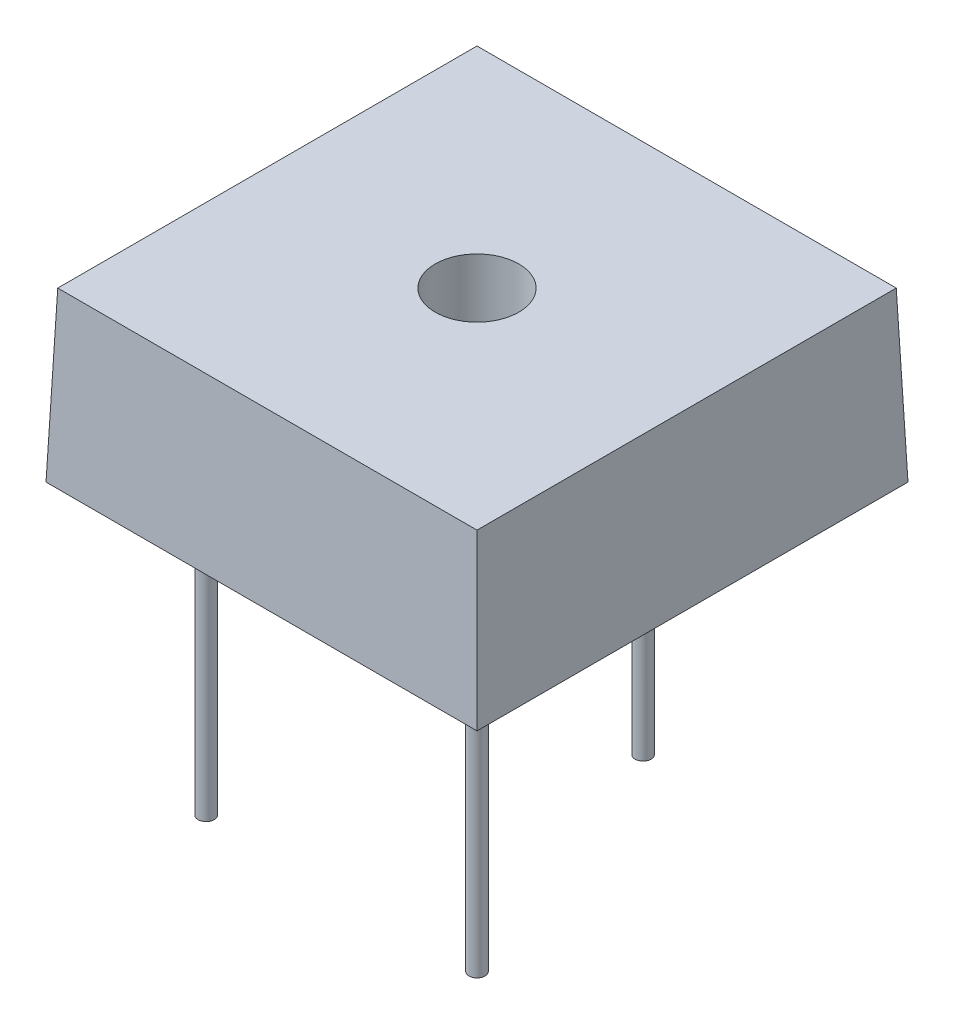
SolidWorks part; units mm, degrees
ref_plane "Front" through (0, 0, 0) normal (0, 0, 1) x (1, 0, 0)
ref_plane "Top" through (0, 0, 0) normal (0, 1, 0) x (1, 0, 0)
ref_plane "Right" through (0, 0, 0) normal (1, 0, 0) x (0, 0, -1)
sketch "Sketch1" plane through (0, 0, 0) normal (0, 1, 0) x (1, 0, 0)
  line L0 (0, 0) -> (0, 14.4) construction
  line L1 (0, 0) -> (14.4, 0) construction
  line L2 (14.4, -14.4) -> (14.4, 14.4)
  line L3 (-14.4, -14.4) -> (-14.4, 14.4)
  line L4 (-14.4, -14.4) -> (14.4, -14.4)
  line L5 (-14.4, 14.4) -> (14.4, 14.4)
  line L6 (0, 14.4) -> (14.4, 14.4) construction
  line L7 (0, -14.4) -> (14.4, -14.4) construction
  line L8 (-14.4, 0) -> (-14.4, 14.4) construction
  line L9 (14.4, 0) -> (14.4, 14.4) construction
  dimension "D1" = 14.4
  dimension "D2" = 14.4
  dimension "D3" = 14.4
  dimension "D4" = 14.4
extrude "Boss-Extrude1" add sketch "Sketch1" along normal blind 11.23 draft 2 contours L5 L3 L4 L2
sketch "Sketch2" plane through (0, 0, 0) normal (0, -1, 0) x (1, 0, 0)
  line L14 (-13.4, -13.4) -> (13.4, -13.4)
  line L15 (13.4, -13.4) -> (13.4, 13.4)
  line L16 (13.4, 13.4) -> (-13.4, 13.4)
  line L17 (-13.4, 13.4) -> (-13.4, -13.4)
  line L18 (-13.4, -13.4) -> (13.4, -13.4)
  line L19 (13.4, -13.4) -> (13.4, 13.4)
  line L20 (13.4, 13.4) -> (-13.4, 13.4)
  line L21 (-13.4, 13.4) -> (-13.4, -13.4)
  circle A0 centre (0, 0) radius 2.795 construction
  circle A1 centre (0, 0) radius 3.795
  dimension "D2" = 5.59
  dimension "D1" = 1
  dimension "D3" = 1
extrude "Cut-Extrude1" cut sketch "Sketch2" against normal blind 0.5
sketch "Sketch3" plane through (0, 0, 0) normal (0, -1, 0) x (1, 0, 0)
  circle A2 centre (0, 0) radius 2.795
  circle A3 centre (0, 0) radius 2.795
  dimension "D1" = 1
extrude "Cut-Extrude2" cut sketch "Sketch3" against normal through all
sketch "Sketch4" plane through (0, 0.5, 0) normal (0, -1, 0) x (1, 0, 0)
  line L0 (0, 0) -> (0, 15.6946) construction
  line L1 (0, 0) -> (-20.8133, 0) construction
  line L2 (-9.05, 0) -> (-9.05, 15.6946) construction
  line L3 (0, 9.05) -> (-20.8133, 9.05) construction
  line L4 (2.05, -9.05) -> (2.05, 15.6946) construction
  line L5 (2.05, 0) -> (2.05, 15.6946) construction
  circle A0 centre (-9.05, 9.05) radius 0.535
  circle A1 centre (9.05, 9.05) radius 0.535
  circle A2 centre (-9.05, -9.05) radius 0.535
  circle A3 centre (2.05, -9.05) radius 0.535
  dimension "D3" = 11.1
  dimension "D1" = 9.05
  dimension "D2" = 9.05
extrude "Boss-Extrude2" add sketch "Sketch4" along normal blind 30.5 from surface at -10.73 starting at face at (0, 11.23, -2.795)
